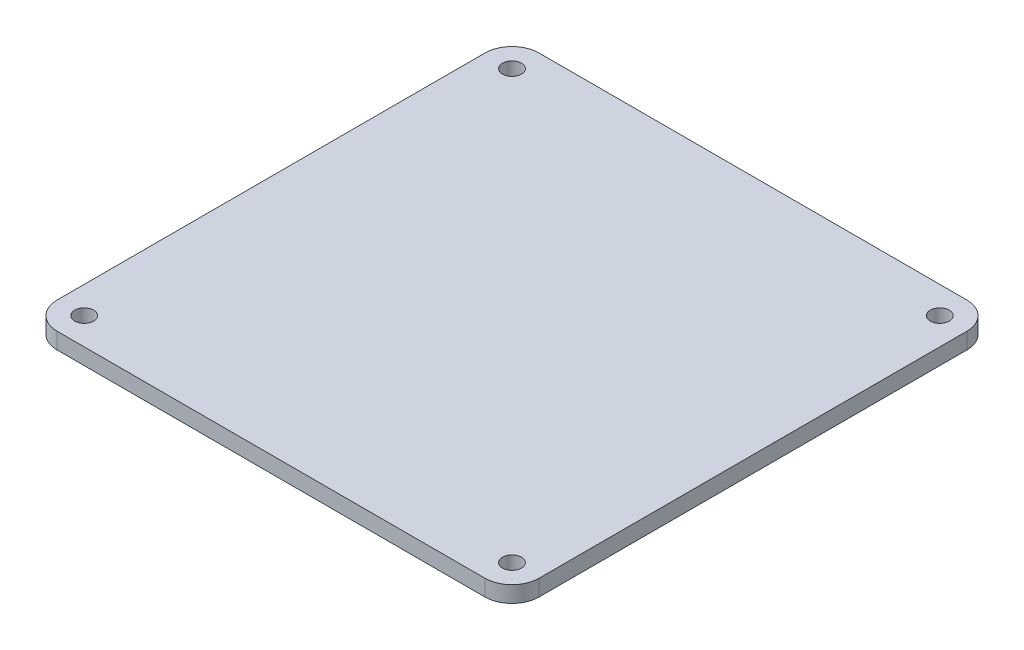
SolidWorks part; units mm, degrees
ref_plane "Front Plane" through (0, 0, 0) normal (0, 0, 1) x (1, 0, 0)
ref_plane "Top Plane" through (0, 0, 0) normal (0, 1, 0) x (1, 0, 0)
ref_plane "Right Plane" through (0, 0, 0) normal (1, 0, 0) x (0, 0, -1)
sketch "Sketch1" plane through (0, 0, 0) normal (0, 1, 0) x (1, 0, 0)
  line L0 (0, 44.494) -> (0, -44.494) construction
  line L1 (-44.494, -44.494) -> (44.494, -44.494) construction
  line L2 (-44.494, -44.494) -> (-44.494, 44.494) construction
  line L3 (-44.494, 44.494) -> (44.494, 44.494) construction
  line L4 (44.494, -44.494) -> (44.494, 44.494) construction
  line L5 (-44.494, -44.494) -> (44.494, 44.494) construction
  line L6 (-44.494, 44.494) -> (44.494, -44.494) construction
  line L7 (-44.494, 0) -> (44.494, 0) construction
  line L8 (0, 44.494) -> (39.494, 44.494)
  line L9 (44.494, 39.494) -> (44.494, 0)
  line L10 (44.494, 0) -> (44.494, -39.494)
  line L11 (39.494, -44.494) -> (0, -44.494)
  line L12 (0, -44.494) -> (-39.494, -44.494)
  line L13 (-44.494, -39.494) -> (-44.494, 0)
  line L14 (-44.494, 0) -> (-44.494, 39.494)
  line L15 (-39.494, 44.494) -> (0, 44.494)
  circle A0 centre (39.494, 39.494) radius 1.75
  circle A1 centre (-39.494, 39.494) radius 1.75
  circle A2 centre (39.494, -39.494) radius 1.75
  circle A3 centre (-39.494, -39.494) radius 1.75
  arc A4 (39.494, 44.494) -> (44.494, 39.494) centre (39.494, 39.494) cw
  arc A5 (44.494, -39.494) -> (39.494, -44.494) centre (39.494, -39.494) cw
  arc A6 (-39.494, -44.494) -> (-44.494, -39.494) centre (-39.494, -39.494) cw
  arc A7 (-44.494, 39.494) -> (-39.494, 44.494) centre (-39.494, 39.494) cw
  point P0 (0, 0)
  dimension "D2" = 3.5
  dimension "D4" = 55.853
  dimension "D3" = 5
  dimension "D1" = 5
  dimension "D5" = 4
extrude "Boss-Extrude1" add sketch "Sketch1" along normal blind 3 contours A7 L14 L13 A6 L12 L11 A5 L10 L9 A4 L8 L15 A3 A1 A0 A2
